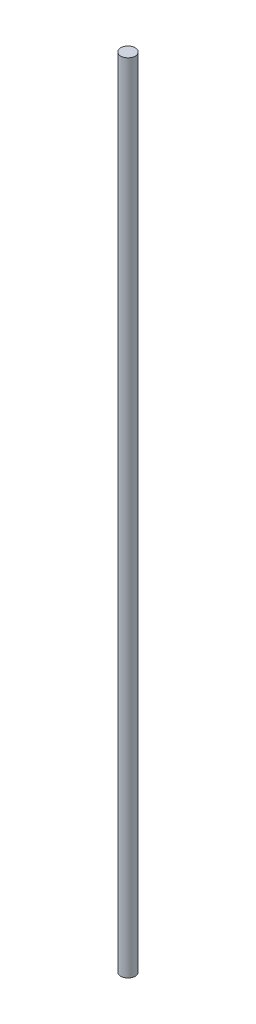
SolidWorks part; units mm, degrees
ref_plane "Front Plane" through (0, 0, 0) normal (0, 0, 1) x (1, 0, 0)
ref_plane "Top Plane" through (0, 0, 0) normal (0, 1, 0) x (1, 0, 0)
ref_plane "Right Plane" through (0, 0, 0) normal (1, 0, 0) x (0, 0, -1)
sketch "Sketch1" plane through (0, 0, 0) normal (0, 1, 0) x (1, 0, 0)
  circle A0 centre (0, 0) radius 2
  dimension "D1" = 4
extrude "Boss-Extrude2" add sketch "Sketch1" along normal blind 220
sketch "Sketch8" plane through (0, 0, 0) normal (0, -1, 0) x (1, 0, 0)
  circle A0 centre (0, 0) radius 2
curve "Helix/Spiral1" pitch 0.7 height 220 turns 314.2857
ref_plane "Plane2" through (-2, 0, 0) normal (-1, 0, 0) x (0, 0, 1)
sketch "Sketch15" plane through (0, 0, 0) normal (-1, 0, 0) x (0, 0, 1)
  line L0 (2, 220) -> (-2, 220) construction
  line L1 (2, 220) -> (-2, 220)
  line L2 (-2, 220) -> (-2, 220.35)
  line L3 (-2, 220.35) -> (0, 220)
  line L4 (0, 220) -> (0, 218.6625)
  line L5 (2, 220) -> (2, 220.35)
  line L6 (2, 220.35) -> (0, 220)
  line L7 (-2, 220) -> (-2, 219.65)
  line L8 (-2, 220) -> (-2, 0) construction
  line L9 (0, 219.65) -> (-2, 220)
  line L10 (-2, 219.65) -> (0, 219.65)
  spline S0 degree 3 number of poles 5030 (1.4142, 0) -> (1.0641, 220) construction
  point P5 (0, 220)
  dimension "D1" = 0.35
  dimension "D2" = 2
  dimension "D3" = 0.35
